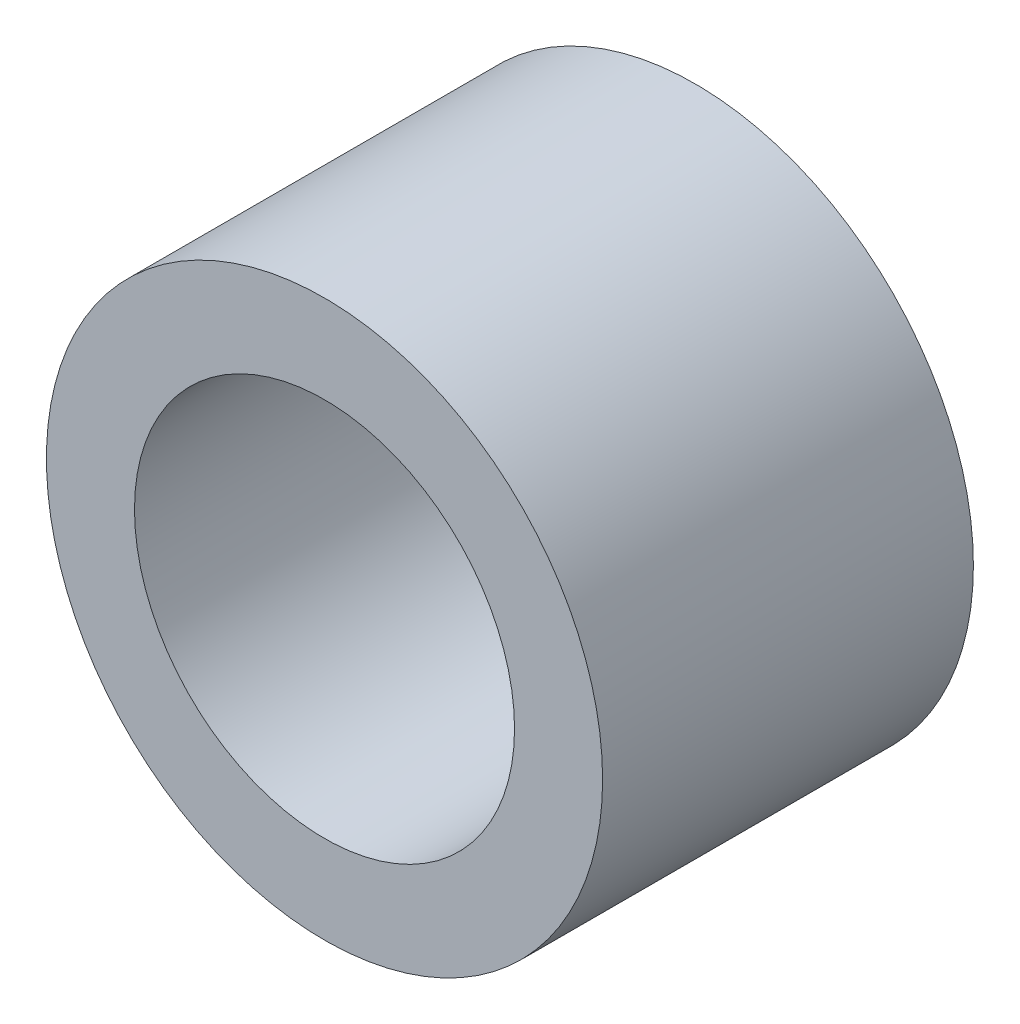
SolidWorks part; units mm, degrees
ref_plane "前视基准面" through (0, 0, 0) normal (0, 0, 1) x (1, 0, 0)
ref_plane "上视基准面" through (0, 0, 0) normal (0, 1, 0) x (1, 0, 0)
ref_plane "右视基准面" through (0, 0, 0) normal (1, 0, 0) x (0, 0, -1)
other "Configuration Table"
sketch "Profile_1" plane through (0, 0, 0) normal (0, 0, 1) x (1, 0, 0)
  circle A0 centre (0, 0) radius 6
  circle A1 centre (0, 0) radius 4.1
extrude "Sleeve" add sketch "Profile_1" along normal blind 8 from offset 0
